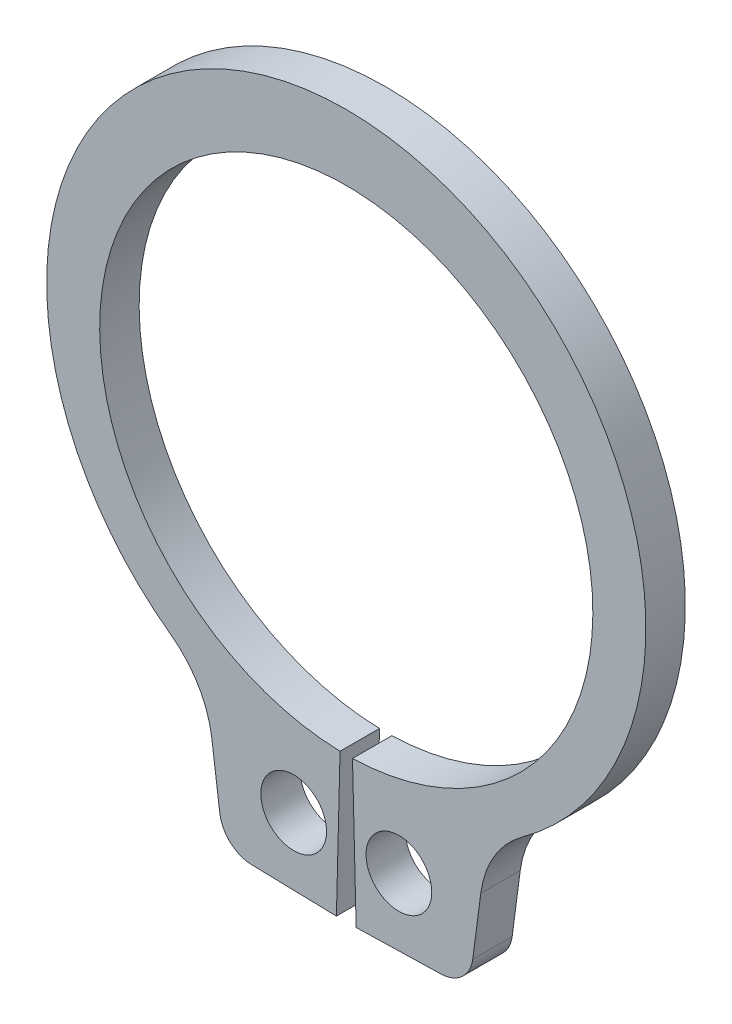
SolidWorks part; units mm, degrees
ref_plane "Plane1" through (0, 0, 0) normal (0, 0, 1) x (1, 0, 0)
ref_plane "Plane2" through (0, 0, 0) normal (0, 1, 0) x (1, 0, 0)
ref_plane "Plane3" through (0, 0, 0) normal (1, 0, 0) x (0, 0, -1)
other "Configuration Table"
sketch "Clipboard" plane through (0, 0, 0) normal (0, 0, 1) x (1, 0, 0)
  line L0 (0, 0) -> (1, 0)
  line L1 (0, 0) -> (0, 0.65)
  line L2 (0, 0) -> (0, -2.2)
  circle A0 centre (0, 0) radius 0.5
  circle A1 centre (0, 0) radius 4
  dimension "HoleDia" = 1
  dimension "ShaftDia" = 8
  dimension "LargeSection" = 1
  dimension "SmallSection" = 0.65
  dimension "LugSection" = 2.2
sketch "BodySke" plane through (0, 0, 0) normal (0, 0, 1) x (1, 0, 0)
  line L0 (-1.5431, 0) -> (1.5431, 0) construction
  line L1 (0, 0) -> (0, 4.75) construction
  line L2 (0.0945, -3.7488) -> (0.15, -5.9481)
  line L3 (-0.0945, -3.7488) -> (-0.15, -5.9481)
  line L4 (0, 0) -> (3.582, -4.751) construction
  line L5 (0, 0) -> (-3.582, -4.751) construction
  line L6 (0.15, -5.9481) -> (1.4398, -5.9156)
  line L7 (2.0456, -4.5487) -> (1.9229, -5.481)
  line L8 (-2.0456, -4.5487) -> (-1.9229, -5.481)
  line L9 (-0.15, -5.9481) -> (-1.4398, -5.9156)
  circle A0 centre (0, 0) radius 3.75 construction
  arc A1 (0.0945, -3.7488) -> (-0.0945, -3.7488) centre (0, 0) ccw
  arc A2 (2.6489, -3.5133) -> (-2.6489, -3.5133) centre (0, 0.1938) ccw construction
  arc A3 (0.15, -5.9481) -> (1.49, -5.7604) centre (0, 0) ccw construction
  arc A4 (2.6729, -3.496) -> (2.0456, -4.5487) centre (3.582, -4.751) ccw
  arc A5 (-2.0456, -4.5487) -> (-2.6729, -3.496) centre (-3.582, -4.751) ccw
  arc A6 (-1.49, -5.7604) -> (-0.15, -5.9481) centre (0, 0) ccw construction
  arc A7 (2.6729, -3.496) -> (-2.6729, -3.496) centre (0, 0.1938) ccw
  arc A8 (-2.0475, -4.5341) -> (2.0475, -4.5341) centre (0, 0) ccw construction
  circle A9 centre (0.8, -4.9103) radius 0.5
  circle A10 centre (-0.8, -4.9103) radius 0.5
  arc A11 (1.9229, -5.481) -> (1.4398, -5.9156) centre (1.4272, -5.4157) cw
  arc A12 (-1.9229, -5.481) -> (-1.4398, -5.9156) centre (-1.4272, -5.4157) ccw
  point P28 (1.9022, -5.6377)
  point P31 (-1.9022, -5.6377)
  dimension "GrooveDia" = 7.5
  dimension "LugRad" = 5.95
  dimension "HoleOffsetRad" = 4.975
  dimension "HoleDia" = 1
  dimension "D3" = 0.5
  dimension "LargeRad" = 4.75
  dimension "SmallRad" = 4.4
  dimension "SmallAngle" = 74.029
  dimension "D2" = 15
  dimension "HoleSpacing" = 1.6
  dimension "Gap" = 0.3
extrude "Body" add sketch "BodySke" against normal blind 0.6
sketch "NotSke" plane through (0, 0, 0) normal (0, 0, 1) x (1, 0, 0)
  line L0 (0.8, -4.4103) -> (0.8, -5.4103)
  line L1 (0.8, -5.4103) -> (-0.8, -5.4103)
  line L2 (-0.8, -5.4103) -> (-0.8, -4.4103)
  line L3 (-0.8, -4.4103) -> (0.8, -4.4103)
  circle A0 centre (0.8, -4.9103) radius 0.5 construction
  circle A1 centre (-0.8, -4.9103) radius 0.5 construction
extrude "Notch" [suppressed] cut sketch "NotSke" against normal through all
equation "' \"ShaftDia@Clipboard\" = 4"
equation "' \"Thickness@Body\" = 0.25"
equation "' \"GrooveDia@BodySke\" = 3.8"
equation "' \"LugSection@Clipboard\" = 1.35"
equation "' \"LargeSection@Clipboard\" = 0.65"
equation "' \"SmallSection@Clipboard\" = 0.4"
equation "' \"HoleDia@Clipboard\" = 0.6"
equation "' \"ShaftDia@Clipboard\" = 15"
equation "' \"Thickness@Body\" = 0.9"
equation "' \"GrooveDia@BodySke\" = 14.15"
equation "' \"LugSection@Clipboard\" = 2.8"
equation "' \"LargeSection@Clipboard\" = 1.8"
equation "' \"SmallSection@Clipboard\" = 1.05"
equation "' \"HoleDia@Clipboard\" = 1.2"
equation "\"Gap@BodySke\" =  \"Thickness@Body\" / 2"
equation "\"LargeRad@BodySke\" =  \"GrooveDia@BodySke\" / 2 +  \"LargeSection@Clipboard\""
equation "\"SmallRad@BodySke\" =  \"GrooveDia@BodySke\" / 2 +  \"SmallSection@Clipboard\""
equation "\"LugRad@BodySke\" = \"GrooveDia@BodySke\" / 2 + \"LugSection@Clipboard\""
equation "\"HoleOffsetRad@BodySke\" = (  \"ShaftDia@Clipboard\" / 2 + \"LugRad@BodySke\" ) / 2"
equation "\"HoleSpacing@BodySke\" = \"Gap@BodySke\"  * 2 +  \"HoleDia@Clipboard\""
equation "\"HoleDia@BodySke\" =  \"HoleDia@Clipboard\""
equation "\"SmallAngle@BodySke\" = atn(\"HoleSpacing@BodySke\" / 2 / sqr(\"HoleOffsetRad@BodySke\"  * \"HoleOffsetRad@BodySke\" - (\"HoleSpacing@BodySke\" / 2) * (\"HoleSpacing@BodySke\" / 2) ))  * 8 * ( 180 / 3.141593)"
